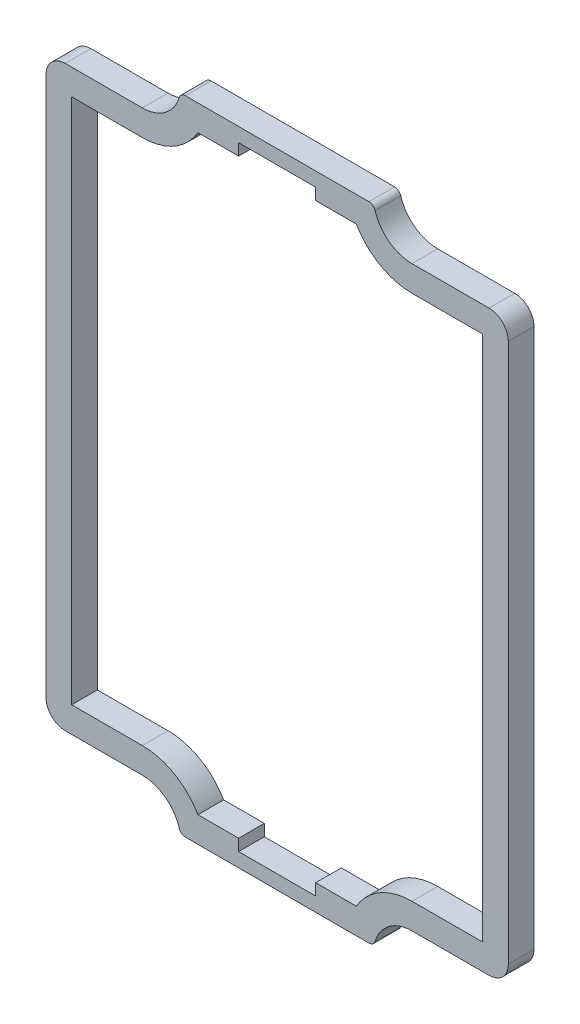
SolidWorks part; units mm, degrees
ref_plane "Face" through (0, 0, 0) normal (0, 0, 1) x (1, 0, 0)
ref_plane "Dessus" through (0, 0, 0) normal (0, 1, 0) x (1, 0, 0)
ref_plane "Droite" through (0, 0, 0) normal (1, 0, 0) x (0, 0, -1)
sketch "Esquisse1" plane through (0, 0, 0) normal (0, 0, 1) x (1, 0, 0)
  line L0 (-16, -20.5) -> (-10.5, -20.5)
  line L1 (3, -23.903) -> (3, -23)
  line L2 (-6.1699, -23) -> (-3, -23)
  line L3 (-3, -23.903) -> (-3, -23)
  line L4 (-16, -20.5) -> (-16, 20.5)
  line L5 (-16, 20.5) -> (-10.5, 20.5)
  line L6 (-6.1699, 23) -> (-3, 23)
  line L7 (-16.5, -22.5) -> (-10.5, -22.5)
  line L9 (-16.5, 22.5) -> (-10.5, 22.5)
  line L16 (0, 0) -> (25.8701, 0) construction
  line L18 (6.1699, -23) -> (3, -23)
  line L20 (-3, -23.903) -> (3, -23.903)
  line L23 (16, -20.5) -> (16, 20.5)
  line L27 (-3, 23.903) -> (3, 23.903)
  line L28 (-3, 23.903) -> (-3, 23)
  line L29 (6.1699, 23) -> (3, 23)
  line L31 (3, 23.903) -> (3, 23)
  line L44 (-7.1459, -25) -> (7.1459, -25)
  line L46 (-7.1459, 25) -> (7.1459, 25)
  line L49 (-18, -21) -> (-18, 21)
  line L50 (18, -21) -> (18, 21)
  line L52 (10.5, 22.5) -> (16.5, 22.5)
  line L59 (10.5, -22.5) -> (16.5, -22.5)
  line L62 (0, 0) -> (0, 33.7336) construction
  line L64 (10.5, -20.5) -> (16, -20.5)
  line L65 (10.5, 20.5) -> (16, 20.5)
  arc A0 (-6.1699, -23) -> (-10.5, -20.5) centre (-10.5, -25.5) ccw construction
  arc A1 (10.5, -20.5) -> (6.1699, -23) centre (10.5, -25.5) ccw construction
  arc A2 (-10.5, 20.5) -> (-6.1699, 23) centre (-10.5, 25.5) ccw construction
  arc A3 (6.1699, 23) -> (10.5, 20.5) centre (10.5, 25.5) ccw construction
  arc A4 (-6.1699, -23) -> (-10.5, -20.5) centre (-10.5, -25.5) ccw
  arc A5 (10.5, -20.5) -> (6.1699, -23) centre (10.5, -25.5) ccw
  arc A6 (-10.5, 20.5) -> (-6.1699, 23) centre (-10.5, 25.5) ccw
  arc A7 (6.1699, 23) -> (10.5, 20.5) centre (10.5, 25.5) ccw
  arc A8 (-18, -21) -> (-16.5, -22.5) centre (-16.5, -21) ccw construction
  arc A9 (16.5, -22.5) -> (18, -21) centre (16.5, -21) ccw construction
  arc A10 (10.5, -22.5) -> (7.6251, -24.6429) centre (10.5, -25.5) ccw construction
  arc A11 (-7.6251, -24.6429) -> (-10.5, -22.5) centre (-10.5, -25.5) ccw construction
  arc A12 (-10.5, 22.5) -> (-7.6251, 24.6429) centre (-10.5, 25.5) ccw construction
  arc A13 (-16.5, 22.5) -> (-18, 21) centre (-16.5, 21) ccw construction
  arc A14 (18, 21) -> (16.5, 22.5) centre (16.5, 21) ccw construction
  arc A15 (7.6251, 24.6429) -> (10.5, 22.5) centre (10.5, 25.5) ccw construction
  arc A16 (-18, -21) -> (-16.5, -22.5) centre (-16.5, -21) ccw
  arc A17 (16.5, -22.5) -> (18, -21) centre (16.5, -21) ccw
  arc A18 (10.5, -22.5) -> (7.6251, -24.6429) centre (10.5, -25.5) ccw
  arc A19 (-7.6251, -24.6429) -> (-10.5, -22.5) centre (-10.5, -25.5) ccw
  arc A20 (-10.5, 22.5) -> (-7.6251, 24.6429) centre (-10.5, 25.5) ccw
  arc A21 (-16.5, 22.5) -> (-18, 21) centre (-16.5, 21) ccw
  arc A22 (18, 21) -> (16.5, 22.5) centre (16.5, 21) ccw
  arc A23 (7.6251, 24.6429) -> (10.5, 22.5) centre (10.5, 25.5) ccw
  arc A24 (7.6251, 24.6429) -> (7.1459, 25) centre (7.1459, 24.5) ccw construction
  arc A25 (-7.1459, 25) -> (-7.6251, 24.6429) centre (-7.1459, 24.5) ccw construction
  arc A26 (7.6251, 24.6429) -> (7.1459, 25) centre (7.1459, 24.5) ccw
  arc A27 (-7.1459, 25) -> (-7.6251, 24.6429) centre (-7.1459, 24.5) ccw
  arc A28 (7.1459, -25) -> (7.6251, -24.6429) centre (7.1459, -24.5) ccw construction
  arc A29 (7.1459, -25) -> (7.6251, -24.6429) centre (7.1459, -24.5) ccw
  arc A30 (-7.6251, -24.6429) -> (-7.1459, -25) centre (-7.1459, -24.5) ccw construction
  arc A31 (-7.6251, -24.6429) -> (-7.1459, -25) centre (-7.1459, -24.5) ccw
  dimension "D1" = 45
  dimension "D2" = 36
  dimension "D3" = 50
  dimension "D4" = 2
  dimension "D5" = 1.5
  dimension "D6" = 21
  dimension "D7" = 25.5
extrude "Base-Extrusion" add sketch "Esquisse1" along normal blind 2
